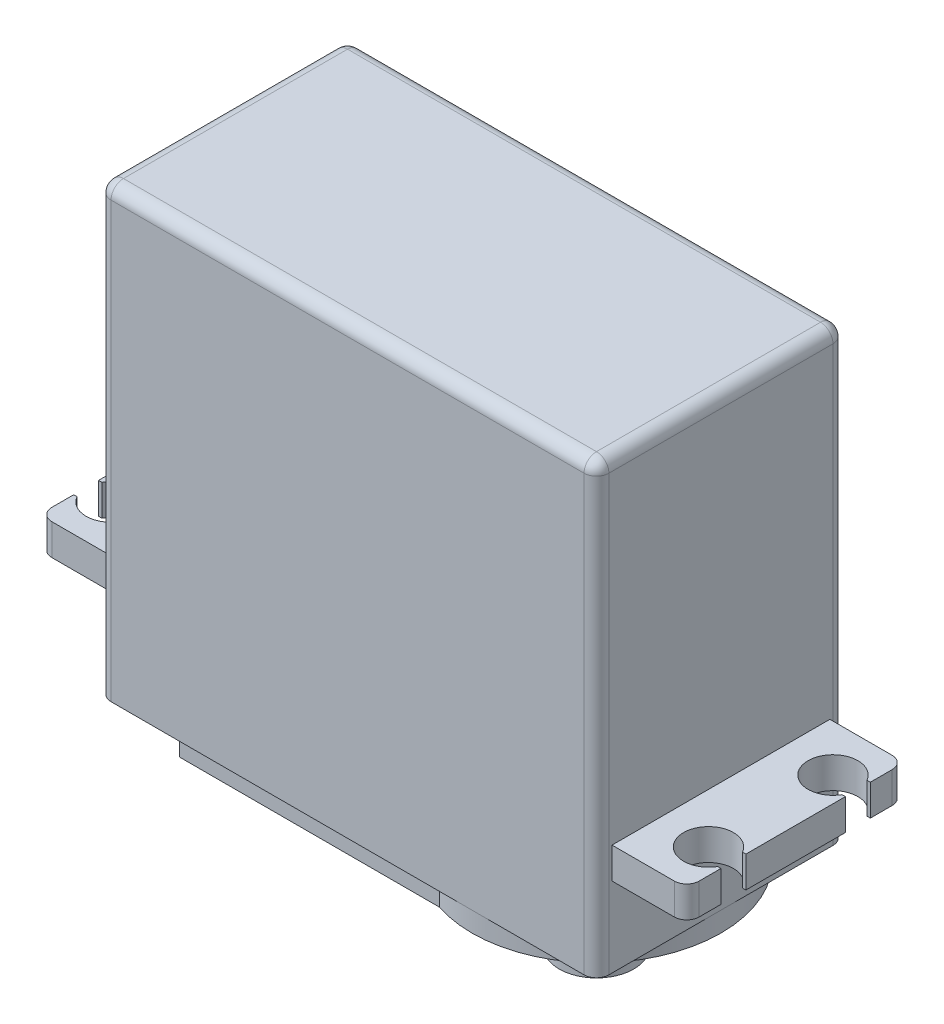
SolidWorks part; units mm, degrees
ref_plane "Ön Düzlem" through (0, 0, 0) normal (0, 0, 1) x (1, 0, 0)
ref_plane "Üst Düzlem" through (0, 0, 0) normal (0, 1, 0) x (1, 0, 0)
ref_plane "Sağ Düzlem" through (0, 0, 0) normal (1, 0, 0) x (0, 0, -1)
sketch "Çizim1" plane through (0, 0, 0) normal (0, 1, 0) x (1, 0, 0)
  line L1 (1, 0) -> (39, 0)
  line L2 (0, 1) -> (0, 19)
  line L3 (1, 20) -> (39, 20)
  line L4 (40, 1) -> (40, 19)
  arc A0 (40, 19) -> (39, 20) centre (39, 19) ccw
  arc A1 (39, 0) -> (40, 1) centre (39, 1) ccw
  arc A2 (1, 0) -> (0, 1) centre (1, 1) cw
  arc A3 (0, 19) -> (1, 20) centre (1, 19) cw
  point P7 (40, 20)
  point P12 (0, 0)
  point P15 (0, 20)
  dimension "D3" = 1
  dimension "D1" = 20
  dimension "D2" = 40
extrude "Yükseklik-Ekstrüzyon1" add sketch "Çizim1" along normal blind 37.5
fillet "Radyus1" radius 1 8 edges at (40, 37.5, -10) (39.7071, 37.5, -0.2929) (20, 37.5, 0) (0.2929, 37.5, -0.2929) (0, 37.5, -10) (0.2929, 37.5, -19.7071) (20, 37.5, -20) (39.7071, 37.5, -19.7071)
ref_plane "Düzlem1" through (0, 10.5, 0) normal (0, 1, 0) x (1, 0, 0)
sketch "Çizim2" plane through (0, 10.5, 0) normal (0, 1, 0) x (1, 0, 0)
  line L0 (0, 10) -> (40, 10) construction
  line L1 (0, 19) -> (0, 1) construction
  line L2 (40, 1) -> (40, 19) construction
  line L3 (-5.7321, 4) -> (-6, 4)
  line L4 (0, 1.25) -> (-5, 1.25)
  line L5 (0, 1.25) -> (0, 18.75)
  line L6 (0, 18.75) -> (-5, 18.75)
  line L7 (-6, 2.25) -> (-6, 4)
  line L8 (40, 1.25) -> (45, 1.25)
  line L9 (40, 1.25) -> (40, 18.75)
  line L10 (40, 18.75) -> (45, 18.75)
  line L11 (46, 2.25) -> (46, 4)
  line L12 (-5.7321, 6) -> (-6, 6)
  line L13 (-5.7321, 14) -> (-6, 14)
  line L14 (-5.7321, 16) -> (-6, 16)
  line L15 (-4, 15) -> (-10.9357, 15) construction
  line L16 (-6, 16) -> (-6, 17.75)
  line L17 (-4, 5) -> (-0.6667, 5) construction
  line L18 (-6, 6) -> (-6, 14)
  line L19 (45.7321, 4) -> (46, 4)
  line L20 (45.7321, 6) -> (46, 6)
  line L21 (45.7321, 14) -> (46, 14)
  line L22 (45.7321, 16) -> (46, 16)
  line L23 (44, 15) -> (50.5715, 15) construction
  line L24 (44, 5) -> (49.3934, 5) construction
  line L25 (46, 16) -> (46, 17.75)
  line L26 (46, 6) -> (46, 14)
  arc A0 (46, 17.75) -> (45, 18.75) centre (45, 17.75) ccw
  arc A1 (46, 2.25) -> (45, 1.25) centre (45, 2.25) cw
  arc A2 (-5, 18.75) -> (-6, 17.75) centre (-5, 17.75) ccw
  arc A3 (-6, 2.25) -> (-5, 1.25) centre (-5, 2.25) ccw
  arc A4 (-5.7321, 4) -> (-5.7321, 6) centre (-4, 5) ccw
  arc A5 (-5.7321, 14) -> (-5.7321, 16) centre (-4, 15) ccw
  arc A6 (45.7321, 6) -> (45.7321, 4) centre (44, 5) ccw
  arc A7 (45.7321, 16) -> (45.7321, 14) centre (44, 15) ccw
  point P18 (46, 1.25)
  point P21 (-6, 18.75)
  point P24 (-6, 1.25)
  dimension "D4" = 1
  dimension "D5" = 4
  dimension "D6" = 4
  dimension "D7" = 4
  dimension "D8" = 4
  dimension "D1" = 17.5
  dimension "D2" = 6
  dimension "D3" = 6
  dimension "D9" = 4
  dimension "D10" = 4
  dimension "D11" = 10
  dimension "D12" = 2
  dimension "D13" = 2
  dimension "D14" = 2
  dimension "D15" = 2
extrude "Yükseklik-Ekstrüzyon3" add sketch "Çizim2" against normal blind 2.5
sketch "Çizim3" plane through (0, 0, 0) normal (0, -1, 0) x (1, 0, 0)
  line L0 (40, -18.75) -> (40, -1.25) construction
  line L1 (1, 0) -> (39, 0) construction
  line L2 (39, -20) -> (1, -20) construction
  line L3 (30, -10) -> (17.9085, -10) construction
  line L4 (27.5, -0.5) -> (6, -0.5)
  line L5 (6, -14) -> (6, -19.5)
  line L6 (27.5, -19.5) -> (6, -19.5)
  line L7 (6, -0.5) -> (6, -6)
  line L11 (40, -19) -> (40, -1)
  line L12 (39, 0) -> (1, 0)
  line L13 (0, -1) -> (0, -19)
  line L14 (1, -20) -> (39, -20)
  line L15 (40, -19) -> (40, -1)
  line L16 (39, 0) -> (1, 0)
  line L17 (0, -1) -> (0, -19)
  line L18 (1, -20) -> (39, -20)
  arc A0 (26.8775, -19.5) -> (26.8775, -0.5) centre (30, -10) ccw
  arc A1 (6, -6) -> (6, -14) centre (11.7446, -10) ccw
  arc A5 (39, -20) -> (40, -19) centre (39, -19) ccw
  arc A6 (40, -1) -> (39, 0) centre (39, -1) ccw
  arc A7 (1, 0) -> (0, -1) centre (1, -1) ccw
  arc A8 (0, -19) -> (1, -20) centre (1, -19) ccw
  arc A9 (39, -20) -> (40, -19) centre (39, -19) ccw
  arc A10 (40, -1) -> (39, 0) centre (39, -1) ccw
  arc A11 (1, 0) -> (0, -1) centre (1, -1) ccw
  arc A12 (0, -19) -> (1, -20) centre (1, -19) ccw
  arc M15 (39, -20) -> (40, -19) centre (39, -19) ccw
  line M16 (40, -19) -> (40, -1)
  arc M17 (40, -1) -> (39, 0) centre (39, -1) ccw
  line M18 (39, 0) -> (1, 0)
  arc M19 (1, 0) -> (0, -1) centre (1, -1) ccw
  line M20 (0, -1) -> (0, -19)
  arc M21 (0, -19) -> (1, -20) centre (1, -19) ccw
  line M22 (1, -20) -> (39, -20)
  dimension "D7" = 7
  dimension "D2" = 0.5
  dimension "D3" = 0.5
  dimension "D5" = 8
  dimension "D6" = 6
  dimension "D1" = 0
extrude "Kes-Ekstrüzyon1" cut sketch "Çizim3" against normal blind 1.6 contours A1 L7 L4 A0 L16 L6 L5 M19 M20 M21 M22 | A0 L18 M15 M16 | A0 L15 M17 M18
sketch "Çizim4" plane through (0, 0, 0) normal (0, -1, 0) x (1, 0, 0)
  circle A0 centre (30, -10) radius 6
  dimension "D1" = 12
extrude "Yükseklik-Ekstrüzyon4" add sketch "Çizim4" along normal blind 1
sketch "Çizim5" plane through (0, -1, 0) normal (0, -1, 0) x (1, 0, 0)
  circle A0 centre (30, -10) radius 5.5
  dimension "D1" = 11
extrude "Yükseklik-Ekstrüzyon5" add sketch "Çizim5" along normal blind 1
sketch "Çizim6" plane through (0, -2, 0) normal (0, -1, 0) x (1, 0, 0)
  circle A0 centre (30, -10) radius 3
  dimension "D1" = 6
extrude "Yükseklik-Ekstrüzyon6" add sketch "Çizim6" along normal blind 4
